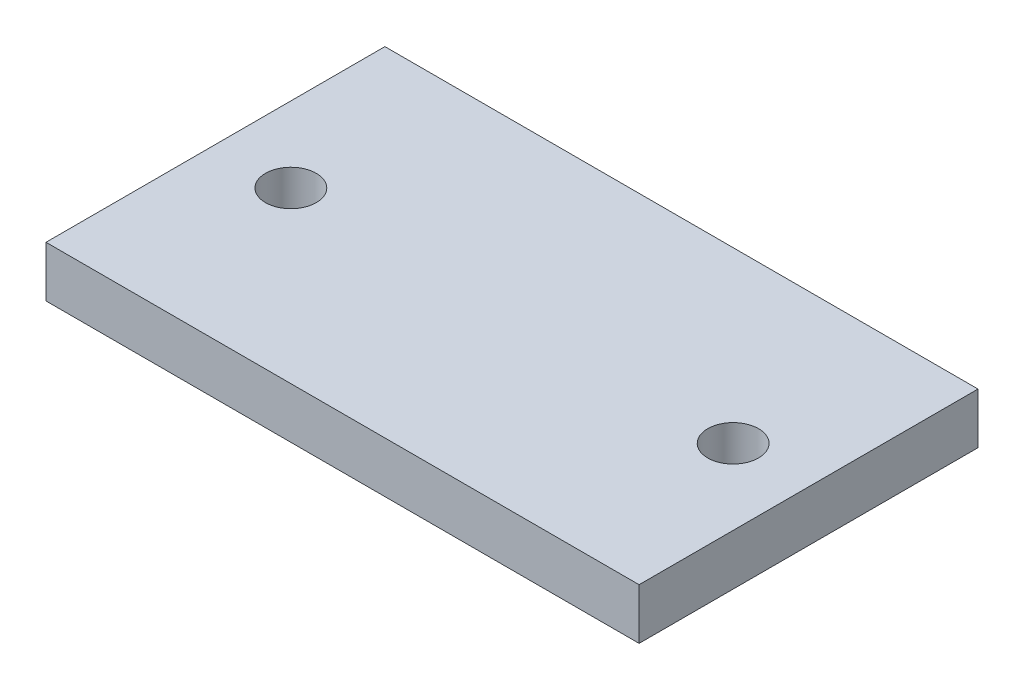
SolidWorks part; units mm, degrees
ref_plane "Front Plane" through (0, 0, 0) normal (0, 0, 1) x (1, 0, 0)
ref_plane "Top Plane" through (0, 0, 0) normal (0, 1, 0) x (1, 0, 0)
ref_plane "Right Plane" through (0, 0, 0) normal (1, 0, 0) x (0, 0, -1)
sketch "Sketch2" plane through (0, 0, 0) normal (0, 1, 0) x (1, 0, 0)
  line L0 (-13.05, 10) -> (-13.05, -10) construction
  line L1 (17.5, -10) -> (-17.5, -10)
  line L2 (17.5, -10) -> (17.5, 10)
  line L3 (17.5, 10) -> (-17.5, 10)
  line L4 (-17.5, -10) -> (-17.5, 10)
  line L5 (17.5, -10) -> (-17.5, 10) construction
  line L6 (17.5, 10) -> (-17.5, -10) construction
  line L7 (13.05, 10) -> (13.05, -10) construction
  line L8 (-13.05, 0) -> (13.05, 0) construction
  circle A0 centre (-13.05, 0) radius 1.5
  circle A1 centre (13.05, 0) radius 1.5
  point P0 (0, 0)
  point P14 (0, 0)
  dimension "D3" = 3
  dimension "D4" = 3
  dimension "D1" = 35
  dimension "D2" = 20
  dimension "D5" = 26.1
extrude "Boss-Extrude1" add sketch "Sketch2" along normal blind 3
